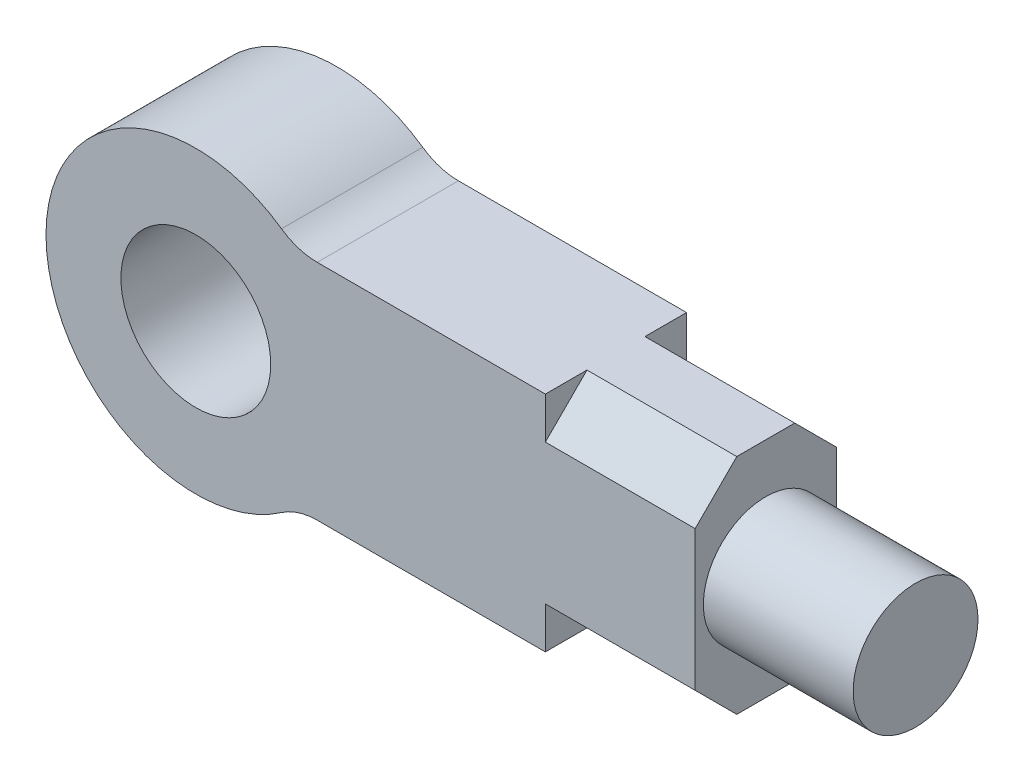
SolidWorks part; units mm, degrees
ref_plane "Front Plane" through (0, 0, 0) normal (0, 0, 1) x (1, 0, 0)
ref_plane "Top Plane" through (0, 0, 0) normal (0, 1, 0) x (1, 0, 0)
ref_plane "Right Plane" through (0, 0, 0) normal (1, 0, 0) x (0, 0, -1)
sketch "Sketch1" plane through (0, 0, 0) normal (0, 0, 1) x (1, 0, 0)
  line L0 (0, 0) -> (61.3996, 0) construction
  line L2 (9.7241, 8.9443) -> (28, 8.9443)
  line L3 (9.7241, -8.9443) -> (28, -8.9443)
  line L4 (28, 8.9443) -> (28, -8.9443)
  circle A1 centre (0, 0) radius 6
  arc A2 (6.864, 9.843) -> (6.864, -9.843) centre (0, 0) ccw
  arc A3 (9.7241, -8.9443) -> (6.864, -9.843) centre (9.7241, -13.9443) ccw
  arc A4 (9.7241, 8.9443) -> (6.864, 9.843) centre (9.7241, 13.9443) cw
  point P11 (8, -8.9443)
  point P14 (8, 8.9443)
  dimension "D1" = 12
  dimension "D2" = 12
  dimension "D5" = 5
  dimension "D3" = 20
  dimension "D4" = 8
extrude "Boss-Extrude1" add sketch "Sketch1" along normal mid plane 11.31
sketch "Sketch2" plane through (28, 0, 0) normal (1, 0, 0) x (0, 0, -1)
  line L0 (-2.3217, 8.9443) -> (-5.655, 5.6109)
  line L1 (0, 55) -> (0, -55) construction
  line L2 (2.3217, 8.9443) -> (5.655, 8.9443)
  line L3 (5.655, 8.9443) -> (5.655, 5.6109)
  line L4 (5.655, -8.9443) -> (5.655, 8.9443)
  line L5 (5.655, 8.9443) -> (-5.655, 8.9443)
  line L6 (-5.655, 8.9443) -> (-5.655, -8.9443)
  line L7 (-5.655, -8.9443) -> (5.655, -8.9443)
  line L9 (-2.3217, 8.9443) -> (-5.655, 8.9443)
  line L10 (-5.655, 8.9443) -> (-5.655, 5.6109)
  line L11 (2.3217, 8.9443) -> (5.655, 5.6109)
  line L12 (55, 0) -> (-55, 0) construction
  line L13 (5.655, -8.9443) -> (5.655, -5.6109)
  line L14 (2.3217, -8.9443) -> (5.655, -8.9443)
  line L15 (2.3217, -8.9443) -> (5.655, -5.6109)
  line L16 (-2.3217, -8.9443) -> (-5.655, -8.9443)
  line L17 (-5.655, -8.9443) -> (-5.655, -5.6109)
  line L18 (-2.3217, -8.9443) -> (-5.655, -5.6109)
  line M9 (5.655, -8.9443) -> (5.655, 8.9443)
  line M10 (5.655, 8.9443) -> (-5.655, 8.9443)
  line M11 (-5.655, 8.9443) -> (-5.655, -8.9443)
  line M12 (-5.655, -8.9443) -> (5.655, -8.9443)
  dimension "D2" = 3.3333
  dimension "D3" = 3.3333
  dimension "D1" = 0
extrude "Boss-Extrude2" add sketch "Sketch2" along normal blind 12 contours L18 L15 L11 L0 M12 M9 M10 M11
sketch "Sketch3" plane through (40, 0, 0) normal (1, 0, 0) x (0, 0, -1)
  circle A0 centre (0, 0) radius 5
  dimension "D1" = 10
extrude "Boss-Extrude3" add sketch "Sketch3" along normal blind 12
equation "\"d\"= 10"
equation "\"d1\"= \"d\""
equation "\"d2\"= 2 * \"d\""
equation "\"d3\"= 1.5 * \"d\""
equation "\"t\"= 1.25 * \"d\""
equation "\"t1\"= 0.75 * \"d\""
equation "\"t2\"= 0.5 * \"d\""
equation "\"D1@Boss-Extrude1\"=11.31"
equation "\"D1@Sketch1\"=\"d\"*1.2"
equation "\"D2@Sketch1\"=\"d\"*1.2"
equation "\"D3@Sketch1\"=\"d2\""
equation "\"D4@Sketch1\"=\"d\"*0.8"
equation "\"D2@Sketch2\"=\"d\"/3"
equation "\"D3@Sketch2\"=\"d\"/3"
equation "\"D1@Boss-Extrude2\"=1.2*\"d\""
equation "\"D1@Sketch3\"=\"d\""
equation "\"D1@Boss-Extrude3\"=1.2*\"d\""
